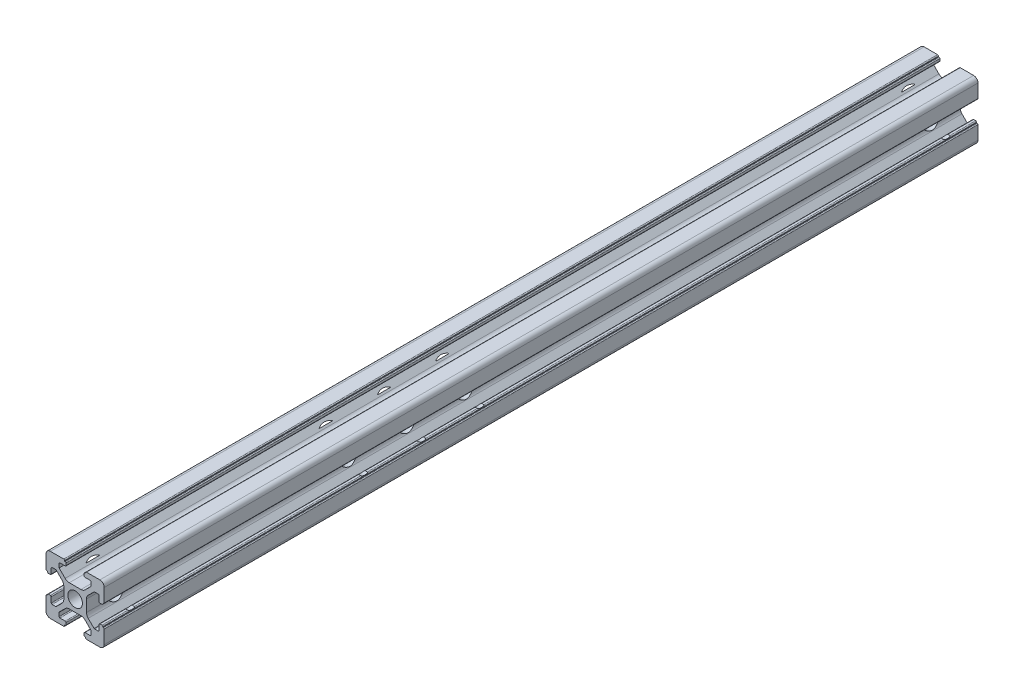
SolidWorks part; units mm, degrees
material "6061 Alloy"
ref_plane "Front Plane" through (0, 0, 0) normal (0, 0, 1) x (1, 0, 0)
ref_plane "Top Plane" through (0, 0, 0) normal (0, 1, 0) x (1, 0, 0)
ref_plane "Right Plane" through (0, 0, 0) normal (1, 0, 0) x (0, 0, -1)
sketch "Sketch1" plane through (0, 0, 0) normal (1, 0, 0) x (0, 0, -1)
  line L0 (-150, 0) -> (150, 0)
  dimension "D1" = 300
other "铝型材 2020(1)"
ref_plane "Plane1" through (0, 0, 150) normal (0, 0, -1) x (0, 1, 0)
sketch "草图1" plane through (0, 0, 150) normal (0, 0, -1) x (0, 1, 0)
  line L0 (3.9, 0) -> (3.9, -2.0109)
  line L1 (4.4858, -3.4251) -> (6.5607, -5.5)
  line L2 (6.5607, -5.5) -> (7.9, -5.5)
  line L3 (8.2, -5.2) -> (8.2, -3.4)
  line L4 (8.5, -3.1) -> (9.2, -3.1)
  line L5 (9.5, -3.4) -> (9.5, -3.6)
  line L6 (9.5, -3.6) -> (9.7, -3.6)
  line L7 (10, -3.9) -> (10, -8.5)
  line L8 (8.5, -10) -> (3.9, -10)
  line L9 (3.1, -9.2) -> (3.1, -8.5)
  line L10 (3.4, -8.2) -> (5.2, -8.2)
  line L11 (5.5, -7.9) -> (5.5, -6.6849)
  line L12 (5.4121, -6.4728) -> (3.4251, -4.4858)
  line L13 (2.0109, -3.9) -> (0, -3.9)
  line L14 (0, -3.9) -> (-2.0109, -3.9)
  line L15 (-3.4251, -4.4858) -> (-5.4121, -6.4728)
  line L16 (-5.5, -6.6849) -> (-5.5, -7.9)
  line L17 (-5.2, -8.2) -> (-3.4, -8.2)
  line L18 (-3.1, -8.5) -> (-3.1, -9.2)
  line L19 (-3.9, -10) -> (-8.5, -10)
  line L20 (-10, -8.5) -> (-10, -3.9)
  line L21 (-9.7, -3.6) -> (-9.5, -3.6)
  line L22 (-9.5, -3.6) -> (-9.5, -3.4)
  line L23 (-9.2, -3.1) -> (-8.5, -3.1)
  line L24 (-8.2, -3.4) -> (-8.2, -5.2)
  line L25 (-7.9, -5.5) -> (-6.6849, -5.5)
  line L26 (-6.4728, -5.4121) -> (-4.4858, -3.4251)
  line L27 (-3.9, -2.0109) -> (-3.9, 0)
  line L28 (-3.9, 0) -> (-3.9, 2.0109)
  line L29 (-4.4858, 3.4251) -> (-6.4728, 5.4121)
  line L30 (-6.6849, 5.5) -> (-7.9, 5.5)
  line L31 (-8.2, 5.2) -> (-8.2, 3.4)
  line L32 (-8.5, 3.1) -> (-9.2, 3.1)
  line L33 (-9.5, 3.4) -> (-9.5, 3.6)
  line L34 (-9.5, 3.6) -> (-9.7, 3.6)
  line L35 (-10, 3.9) -> (-10, 8.5)
  line L36 (-8.5, 10) -> (-3.9, 10)
  line L37 (-3.6, 9.7) -> (-3.6, 9.5)
  line L38 (-3.6, 9.5) -> (-3.4, 9.5)
  line L39 (-3.1, 9.2) -> (-3.1, 8.5)
  line L40 (-3.4, 8.2) -> (-5.2, 8.2)
  line L41 (-5.5, 7.9) -> (-5.5, 6.6849)
  line L42 (-5.4121, 6.4728) -> (-3.4251, 4.4858)
  line L43 (-2.0109, 3.9) -> (0, 3.9)
  line L44 (0, 3.9) -> (2.0109, 3.9)
  line L45 (3.4251, 4.4858) -> (5.4121, 6.4728)
  line L46 (5.5, 6.6849) -> (5.5, 7.9)
  line L47 (5.2, 8.2) -> (3.4, 8.2)
  line L48 (3.1, 8.5) -> (3.1, 9.2)
  line L49 (3.4, 9.5) -> (3.6, 9.5)
  line L50 (3.6, 9.5) -> (3.6, 9.7)
  line L51 (3.9, 10) -> (8.5, 10)
  line L52 (10, 8.5) -> (10, 3.9)
  line L53 (9.7, 3.6) -> (9.5, 3.6)
  line L54 (9.5, 3.6) -> (9.5, 3.4)
  line L55 (9.2, 3.1) -> (8.5, 3.1)
  line L56 (8.2, 3.4) -> (8.2, 5.2)
  line L57 (7.9, 5.5) -> (6.6849, 5.5)
  line L58 (6.4728, 5.4121) -> (4.4858, 3.4251)
  line L59 (3.9, 2.0109) -> (3.9, 0)
  circle A0 centre (0, 0) radius 2.5
  arc A1 (3.9, -2.0109) -> (4.4858, -3.4251) centre (5.9, -2.0109) ccw
  arc A2 (7.9, -5.5) -> (8.2, -5.2) centre (7.9, -5.2) ccw
  arc A3 (8.5, -3.1) -> (8.2, -3.4) centre (8.5, -3.4) ccw
  arc A4 (9.5, -3.4) -> (9.2, -3.1) centre (9.2, -3.4) ccw
  arc A5 (10, -3.9) -> (9.7, -3.6) centre (9.7, -3.9) ccw
  arc A6 (8.5, -10) -> (10, -8.5) centre (8.5, -8.5) ccw
  arc A7 (3.6, -9.7) -> (3.9, -10) centre (3.9, -9.7) ccw
  arc A8 (3.6, -9.7) -> (3.4, -9.5) centre (3.4, -9.7) ccw
  arc A9 (3.1, -9.2) -> (3.4, -9.5) centre (3.4, -9.2) ccw
  arc A10 (3.4, -8.2) -> (3.1, -8.5) centre (3.4, -8.5) ccw
  arc A11 (5.2, -8.2) -> (5.5, -7.9) centre (5.2, -7.9) ccw
  arc A12 (5.5, -6.6849) -> (5.4121, -6.4728) centre (5.2, -6.6849) ccw
  arc A13 (3.4251, -4.4858) -> (2.0109, -3.9) centre (2.0109, -5.9) ccw
  arc A14 (-2.0109, -3.9) -> (-3.4251, -4.4858) centre (-2.0109, -5.9) ccw
  arc A15 (-5.4121, -6.4728) -> (-5.5, -6.6849) centre (-5.2, -6.6849) ccw
  arc A16 (-5.5, -7.9) -> (-5.2, -8.2) centre (-5.2, -7.9) ccw
  arc A17 (-3.1, -8.5) -> (-3.4, -8.2) centre (-3.4, -8.5) ccw
  arc A18 (-3.4, -9.5) -> (-3.1, -9.2) centre (-3.4, -9.2) ccw
  arc A19 (-3.4, -9.5) -> (-3.6, -9.7) centre (-3.4, -9.7) ccw
  arc A20 (-3.9, -10) -> (-3.6, -9.7) centre (-3.9, -9.7) ccw
  arc A21 (-10, -8.5) -> (-8.5, -10) centre (-8.5, -8.5) ccw
  arc A22 (-9.7, -3.6) -> (-10, -3.9) centre (-9.7, -3.9) ccw
  arc A23 (-9.2, -3.1) -> (-9.5, -3.4) centre (-9.2, -3.4) ccw
  arc A24 (-8.2, -3.4) -> (-8.5, -3.1) centre (-8.5, -3.4) ccw
  arc A25 (-8.2, -5.2) -> (-7.9, -5.5) centre (-7.9, -5.2) ccw
  arc A26 (-6.6849, -5.5) -> (-6.4728, -5.4121) centre (-6.6849, -5.2) ccw
  arc A27 (-4.4858, -3.4251) -> (-3.9, -2.0109) centre (-5.9, -2.0109) ccw
  arc A28 (-3.9, 2.0109) -> (-4.4858, 3.4251) centre (-5.9, 2.0109) ccw
  arc A29 (-6.4728, 5.4121) -> (-6.6849, 5.5) centre (-6.6849, 5.2) ccw
  arc A30 (-7.9, 5.5) -> (-8.2, 5.2) centre (-7.9, 5.2) ccw
  arc A31 (-8.5, 3.1) -> (-8.2, 3.4) centre (-8.5, 3.4) ccw
  arc A32 (-9.5, 3.4) -> (-9.2, 3.1) centre (-9.2, 3.4) ccw
  arc A33 (-10, 3.9) -> (-9.7, 3.6) centre (-9.7, 3.9) ccw
  arc A34 (-8.5, 10) -> (-10, 8.5) centre (-8.5, 8.5) ccw
  arc A35 (-3.6, 9.7) -> (-3.9, 10) centre (-3.9, 9.7) ccw
  arc A36 (-3.1, 9.2) -> (-3.4, 9.5) centre (-3.4, 9.2) ccw
  arc A37 (-3.4, 8.2) -> (-3.1, 8.5) centre (-3.4, 8.5) ccw
  arc A38 (-5.2, 8.2) -> (-5.5, 7.9) centre (-5.2, 7.9) ccw
  arc A39 (-5.5, 6.6849) -> (-5.4121, 6.4728) centre (-5.2, 6.6849) ccw
  arc A40 (-3.4251, 4.4858) -> (-2.0109, 3.9) centre (-2.0109, 5.9) ccw
  arc A41 (2.0109, 3.9) -> (3.4251, 4.4858) centre (2.0109, 5.9) ccw
  arc A42 (5.4121, 6.4728) -> (5.5, 6.6849) centre (5.2, 6.6849) ccw
  arc A43 (5.5, 7.9) -> (5.2, 8.2) centre (5.2, 7.9) ccw
  arc A44 (3.1, 8.5) -> (3.4, 8.2) centre (3.4, 8.5) ccw
  arc A45 (3.4, 9.5) -> (3.1, 9.2) centre (3.4, 9.2) ccw
  arc A46 (3.9, 10) -> (3.6, 9.7) centre (3.9, 9.7) ccw
  arc A47 (10, 8.5) -> (8.5, 10) centre (8.5, 8.5) ccw
  arc A48 (9.7, 3.6) -> (10, 3.9) centre (9.7, 3.9) ccw
  arc A49 (9.2, 3.1) -> (9.5, 3.4) centre (9.2, 3.4) ccw
  arc A50 (8.2, 3.4) -> (8.5, 3.1) centre (8.5, 3.4) ccw
  arc A51 (8.2, 5.2) -> (7.9, 5.5) centre (7.9, 5.2) ccw
  arc A52 (6.6849, 5.5) -> (6.4728, 5.4121) centre (6.6849, 5.2) ccw
  arc A53 (4.4858, 3.4251) -> (3.9, 2.0109) centre (5.9, 2.0109) ccw
  point P0 (-10, 10)
  point P1 (10, 10)
  point P2 (10, -10)
  point P171 (-10, -10)
  point P172 (-10, 0)
  point P173 (10, 0)
  point P174 (0, -10)
  point P175 (0, 10)
  point P176 (0, 0)
  point P177 (0, 0)
sketch "Sketch2" plane through (-10, 0, 0) normal (-1, 0, 0) x (0, 0, 1)
  line L0 (150, 0) -> (40, 0) construction
  line L1 (150, -2.0109) -> (150, 2.0109) construction
  line L2 (-150, 0) -> (-140, 0) construction
  line L3 (-150, -2.0109) -> (-150, 2.0109) construction
  circle A0 centre (40, 0) radius 3.3
  circle A1 centre (20, 0) radius 3.3
  circle A2 centre (60, 0) radius 3.3
  circle A3 centre (-140, 0) radius 3.3
  circle A4 centre (140, 0) radius 3.3
  dimension "D1" = 6.6
  dimension "D3" = 20
  dimension "D4" = 20
  dimension "D5" = 10
  dimension "D6" = 10
  dimension "D2" = 110
extrude "Cut-Extrude1" cut sketch "Sketch2" against normal through all
sketch "Sketch3" plane through (-10, 0, 0) normal (-1, 0, 0) x (0, 0, 1)
  circle A0 centre (20, 0) radius 5.5
  circle A1 centre (40, 0) radius 5.5
  circle A2 centre (60, 0) radius 5.5
  circle A3 centre (-140, 0) radius 5.5
  circle A4 centre (140, 0) radius 5.5
  dimension "D1" = 11
extrude "Cut-Extrude2" cut sketch "Sketch3" against normal up to vertex (6.1 mm away) up to point (-3.9, 2.0109, -150)
